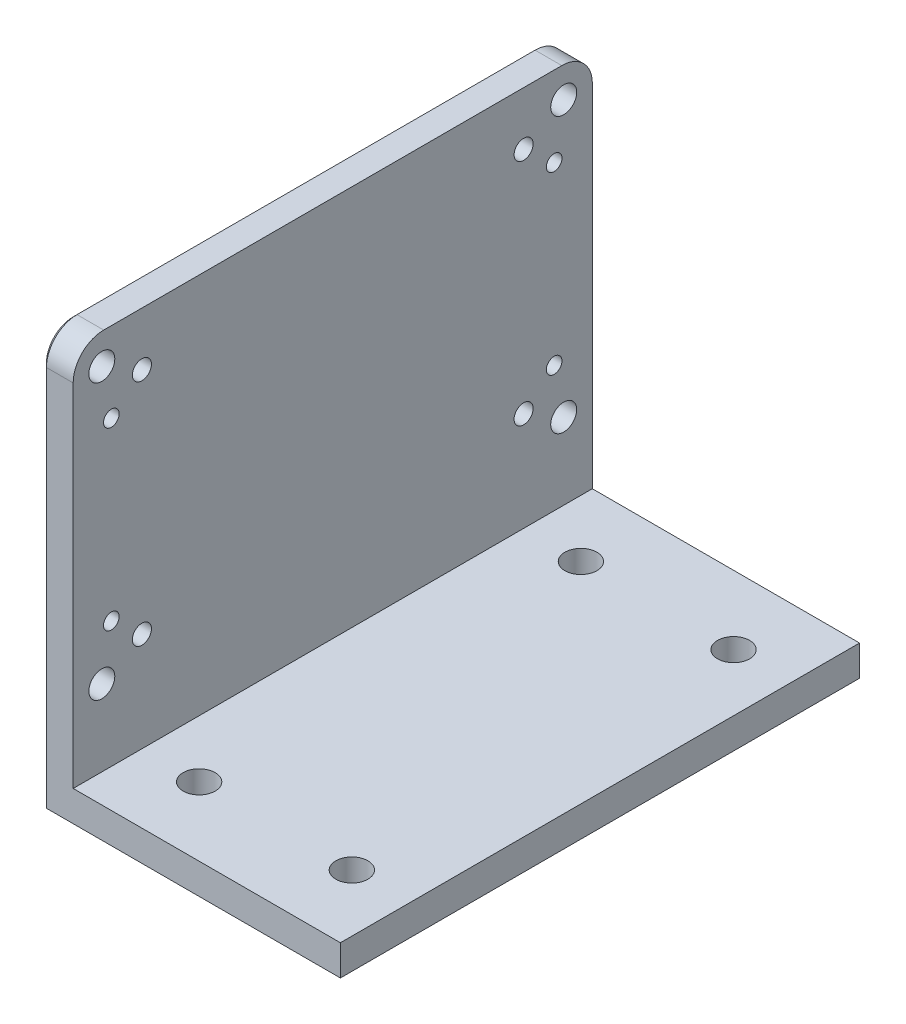
SolidWorks part; units mm, degrees
material "6061-T6 (SS)"
ref_plane "Front Plane" through (0, 0, 0) normal (0, 0, 1) x (1, 0, 0)
ref_plane "Top Plane" through (0, 0, 0) normal (0, 1, 0) x (1, 0, 0)
ref_plane "Right Plane" through (0, 0, 0) normal (1, 0, 0) x (0, 0, -1)
sketch "Sketch1" plane through (0, 0, 0) normal (0, 0, 1) x (1, 0, 0)
  line L0 (0, 0) -> (39, 0)
  line L1 (39, 0) -> (39, 4)
  line L2 (39, 4) -> (4, 4)
  line L3 (4, 4) -> (4, 54)
  line L4 (4, 54) -> (0, 54)
  line L5 (0, 54) -> (0, 0)
  dimension "D1" = 50
  dimension "D2" = 35
  dimension "D3" = 4
extrude "Boss-Extrude1" add sketch "Sketch1" along normal blind 68
sketch "Sketch2" plane through (4, 0, 0) normal (1, 0, 0) x (0, 0, -1)
  line L0 (-34, 32) -> (-34, 54) construction
  line L1 (-64.25, 50) -> (-3.75, 50) construction
  line L2 (-64.25, 50) -> (-64.25, 14) construction
  line L3 (-64.25, 14) -> (-3.75, 14) construction
  line L4 (-3.75, 50) -> (-3.75, 14) construction
  line L5 (-64.25, 50) -> (-3.75, 14) construction
  line L6 (-64.25, 14) -> (-3.75, 50) construction
  line L7 (-68, 54) -> (0, 54) construction
  point P0 (-34, 32)
  dimension "D1" = 60.5
  dimension "D2" = 36
  dimension "D3" = 4
hole_wizard "M3 Clearance Hole1" positions "Sketch4" profile "Sketch3" hole size "M3" standard "ANSI Metric"
sketch "Sketch4" plane through (4, 0, 0) normal (1, 0, 0) x (0, 0, -1)
  point P0 (-64.25, 50)
  point P3 (-3.75, 50)
  point P6 (-3.75, 14)
  point P9 (-64.25, 14)
sketch "Sketch3" plane through (4, 50, 64.25) normal (0, 1, 0) x (0, 0, -1)
  line L0 (0, 0) -> (0, 6.0215)
  line L1 (0, 6.0215) -> (1.7, 5)
  line L2 (1.7, 5) -> (1.7, 0)
  line L5 (1.7, 0) -> (0, 0)
  line L10 (0, 6.0215) -> (-1.7, 5) construction
  line L11 (0, -6.35) -> (0, 107.95) construction
  dimension "Hole Dia." = 3.4
  dimension "Hole Depth" = 5
  dimension "Drill Angle" = 118
sketch "Sketch5" plane through (0, 4, 0) normal (0, 1, 0) x (1, 0, 0)
  line L0 (21.5, 0) -> (21.5, -68) construction
  line L1 (39, 0) -> (4, 0) construction
  line L2 (39, -68) -> (4, -68) construction
  line L3 (4, -34) -> (39, -34) construction
  line L4 (4, -68) -> (4, 0) construction
  line L5 (39, -68) -> (39, 0) construction
  line L7 (11.5, -59) -> (31.5, -59) construction
  line L8 (11.5, -59) -> (11.5, -9) construction
  line L9 (11.5, -9) -> (31.5, -9) construction
  line L10 (31.5, -59) -> (31.5, -9) construction
  line L11 (11.5, -59) -> (31.5, -9) construction
  line L12 (11.5, -9) -> (31.5, -59) construction
  point P12 (21.5, -34)
  dimension "D1" = 20
  dimension "D2" = 50
hole_wizard "M5x0.8 Tapped Hole1" positions "Sketch7" profile "Sketch6" tap size "M5x0.8" standard "ANSI Metric"
sketch "Sketch7" plane through (0, 4, 0) normal (0, 1, 0) x (1, 0, 0)
  point P0 (31.5, -59)
  point P3 (11.5, -59)
  point P6 (11.5, -9)
  point P9 (31.5, -9)
sketch "Sketch6" plane through (31.5, 4, 59) normal (1, 0, 0) x (0, 0, 1)
  line L0 (0, 0) -> (0, 15.2618)
  line L1 (0, 15.2618) -> (2.1, 14)
  line L2 (2.1, 14) -> (2.1, 0)
  line L5 (2.1, 0) -> (0, 0)
  line L10 (0, 15.2618) -> (-2.1, 14) construction
  line L11 (0, -6.35) -> (0, 107.95) construction
  dimension "Tap Drill Dia." = 4.2
  dimension "Tap Drill Depth" = 14
  dimension "Drill Angle" = 118
fillet "Fillet1" radius 4 2 edges at (2, 54, 68) (2, 54, 0)
chamfer "Chamfer1" distance 0.5 angle 45 5 edges at (0, 25, 68) (0, 52.8284, 66.8284) (0, 54, 34) (0, 52.8284, 1.1716) (0, 25, 0)
sketch "Sketch8" plane through (0, 0, 0) normal (-1, 0, 0) x (0, 0, 1)
  line L0 (34, 0) -> (34, 32) construction
  line L1 (5, 20.5) -> (63, 20.5)
  line L2 (5, 20.5) -> (5, 43.5)
  line L3 (5, 43.5) -> (63, 43.5)
  line L4 (63, 20.5) -> (63, 43.5)
  line L5 (5, 20.5) -> (63, 43.5) construction
  line L6 (5, 43.5) -> (63, 20.5) construction
  line L7 (67.5, 0) -> (0.5, 0) construction
  line L8 (3.75, 50) -> (64.25, 14) construction
  point P0 (34, 32)
  point P13 (34, 32)
  dimension "D1" = 58
  dimension "D2" = 23
hole_wizard "M2.5x0.45 Tapped Hole1" positions "Sketch10" profile "Sketch9" tap size "M2.5x0.45" standard "ANSI Metric"
sketch "Sketch10" plane through (0, 0, 0) normal (-1, 0, 0) x (0, 0, 1)
  point P0 (5, 43.5)
  point P3 (63, 43.5)
  point P6 (63, 20.5)
  point P9 (5, 20.5)
sketch "Sketch9" plane through (0, 43.5, 5) normal (0, 1, 0) x (0, 0, 1)
  line L0 (0, 0) -> (0, 7.8659)
  line L1 (0, 7.8659) -> (1.025, 7.25)
  line L2 (1.025, 7.25) -> (1.025, 0)
  line L5 (1.025, 0) -> (0, 0)
  line L10 (0, 7.8659) -> (-1.025, 7.25) construction
  line L11 (0, -6.35) -> (0, 107.95) construction
  dimension "Tap Drill Dia." = 2.05
  dimension "Tap Drill Depth" = 7.25
  dimension "Drill Angle" = 118
sketch "Sketch11" plane through (0, 0, 0) normal (-1, 0, 0) x (0, 0, 1)
  line L1 (59, 17) -> (9, 17)
  line L2 (59, 17) -> (59, 47)
  line L3 (59, 47) -> (9, 47)
  line L4 (9, 17) -> (9, 47)
  line L5 (59, 17) -> (9, 47) construction
  line L6 (59, 47) -> (9, 17) construction
  point P0 (34, 32)
  dimension "D1" = 50
  dimension "D2" = 30
hole_wizard "M3x0.5 Tapped Hole3" positions "Sketch13" profile "Sketch12" tap size "M3x0.5" standard "ANSI Metric"
sketch "Sketch13" plane through (0, 0, 0) normal (-1, 0, 0) x (0, 0, 1)
  point P0 (9, 17)
  point P3 (9, 47)
  point P6 (59, 47)
  point P9 (59, 17)
sketch "Sketch12" plane through (0, 17, 9) normal (0, 1, 0) x (0, 0, 1)
  line L0 (0, 0) -> (0, 9.2511)
  line L1 (0, 9.2511) -> (1.25, 8.5)
  line L2 (1.25, 8.5) -> (1.25, 0)
  line L5 (1.25, 0) -> (0, 0)
  line L10 (0, 9.2511) -> (-1.25, 8.5) construction
  line L11 (0, -6.35) -> (0, 107.95) construction
  dimension "Tap Drill Dia." = 2.5
  dimension "Tap Drill Depth" = 8.5
  dimension "Drill Angle" = 118
